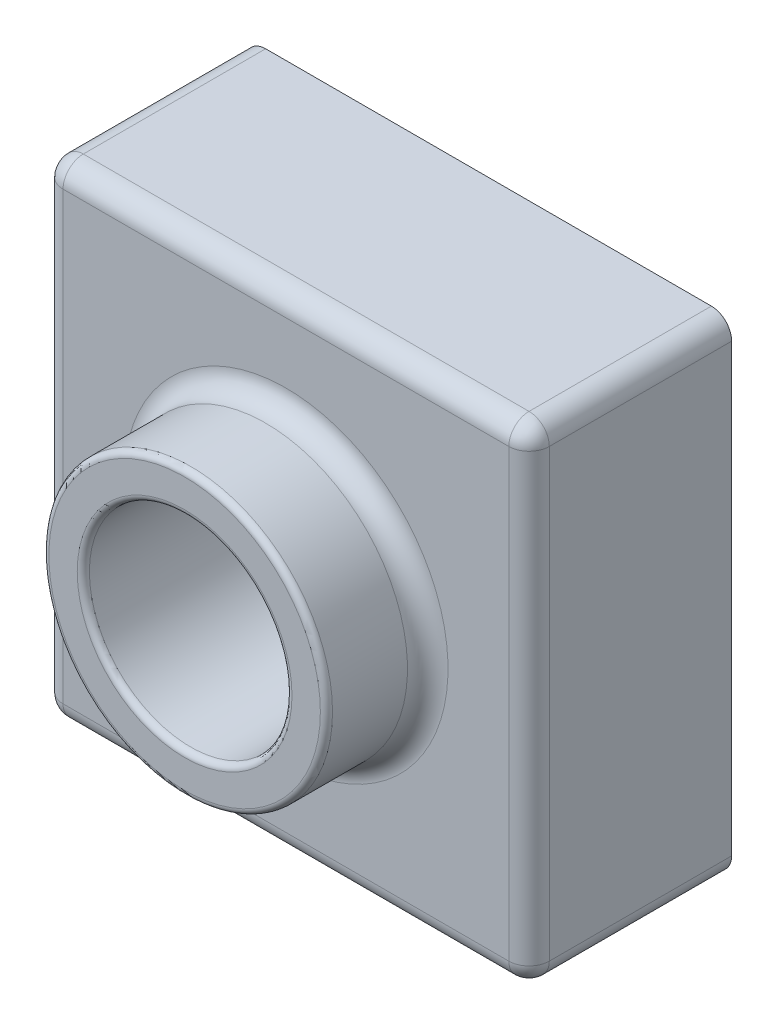
SolidWorks part; units mm, degrees
material "Chrome Stainless Steel"
ref_plane "Front Plane" through (0, 0, 0) normal (0, 0, 1) x (1, 0, 0)
ref_plane "Top Plane" through (0, 0, 0) normal (0, 1, 0) x (1, 0, 0)
ref_plane "Right Plane" through (0, 0, 0) normal (1, 0, 0) x (0, 0, -1)
sketch "Sketch1" plane through (0, 0, 0) normal (0, 0, 1) x (1, 0, 0)
  line L1 (0, 0) -> (120, 0)
  line L2 (0, 0) -> (0, 120)
  line L3 (0, 120) -> (120, 120)
  line L4 (120, 0) -> (120, 120)
  dimension "D1" = 120
extrude "Boss-Extrude1" add sketch "Sketch1" along normal blind 50
sketch "Sketch2" plane through (0, 0, 50) normal (0, 0, 1) x (1, 0, 0)
  line L0 (0, 0) -> (120, 120) construction
  circle A0 centre (60, 60) radius 35
  dimension "D1" = 70
extrude "Boss-Extrude2" add sketch "Sketch2" along normal blind 25
sketch "Sketch3" plane through (0, 0, 75) normal (0, 0, 1) x (1, 0, 0)
  line L0 (25, 60) -> (95, 60) construction
  circle A0 centre (60, 60) radius 35 construction
  circle A1 centre (60, 60) radius 35 construction
  circle A2 centre (60, 60) radius 25
  dimension "D1" = 50
extrude "Cut-Extrude1" cut sketch "Sketch3" against normal through all both and the other way through all
fillet "Fillet1" radius 5 9 edges at (120, 0, 25) (120, 120, 25) (60, 120, 50) (120, 60, 50) (60, 0, 50) (0, 60, 50) (95, 60, 50) (0, 120, 25) (0, 0, 25)
fillet "Fillet2" radius 1.5 2 edges at (95, 60, 75) (85, 60, 75)
shell "Shell1" thickness 2
